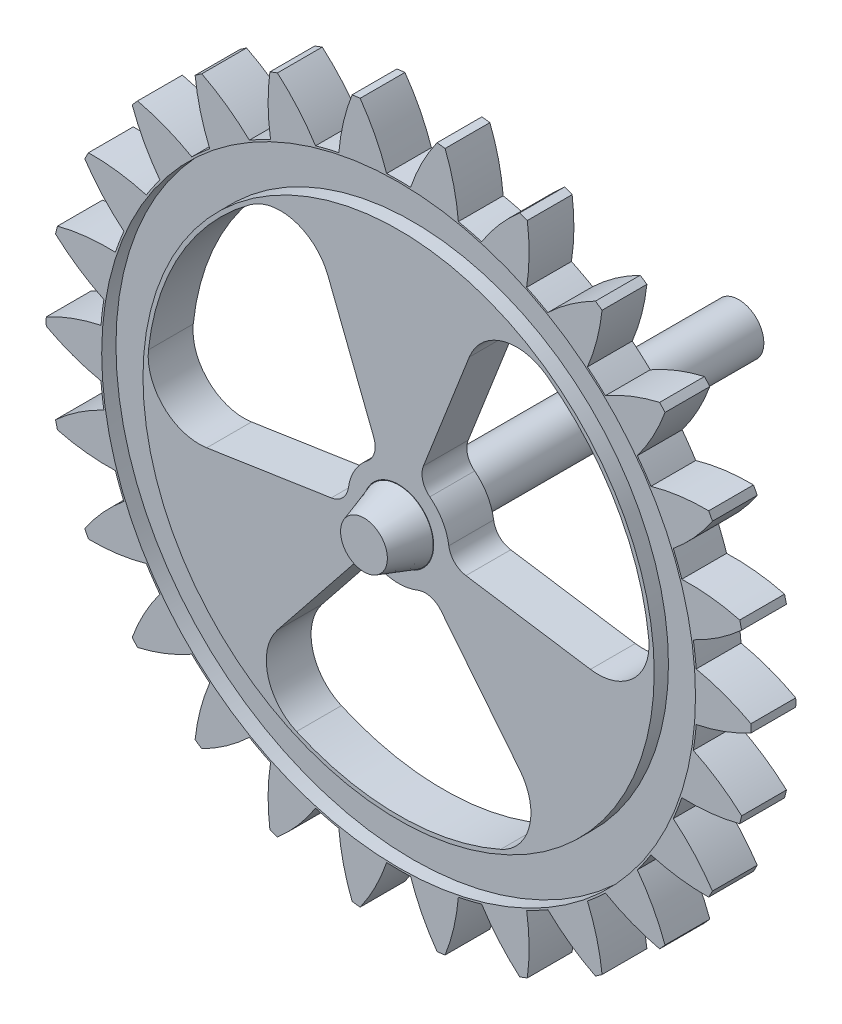
SolidWorks part; units mm, degrees
ref_plane "Plan de face" through (0, 0, 0) normal (0, 0, 1) x (1, 0, 0)
ref_plane "Plan de dessus" through (0, 0, 0) normal (0, 1, 0) x (1, 0, 0)
ref_plane "Plan de droite" through (0, 0, 0) normal (1, 0, 0) x (0, 0, -1)
sketch "Esquisse1" plane through (0, 0, 0) normal (0, 0, 1) x (1, 0, 0)
  circle A0 centre (0, 0) radius 3.4597
  circle A1 centre (0, 0) radius 0.3447
extrude "Boss.-Extru.1" add sketch "Esquisse1" along normal blind 0.44
sketch "Esquisse2" plane through (0, 0, 0.44) normal (0, 0, 1) x (1, 0, 0)
  line L0 (0, 0) -> (0, 4.2515) construction
  arc A0 (0.4748, 3.565) -> (-0.4748, 3.565) centre (0, 0) ccw
  arc A1 (0.1178, 2.9293) -> (-0.1178, 2.9293) centre (0, 0) ccw
  arc A2 (0.4748, 3.565) -> (0.1178, 2.9293) centre (1.9916, 2.2952) ccw
  arc A3 (-0.4748, 3.565) -> (-0.1178, 2.9293) centre (-1.9916, 2.2952) cw
extrude "Enlèv. mat.-Extru.1" cut sketch "Esquisse2" against normal blind 0.44
pattern_circular "Répétition circulaire1" count 26 over 360 about axis through (0, 0, 0) along (0, 0, 1) of "Enlèv. mat.-Extru.1"
sketch "Esquisse3" plane through (0, 0, 0.44) normal (0, 0, 1) x (1, 0, 0)
  line L0 (0, 0) -> (0, 2.47) construction
  line L1 (0.6941, 1.7745) -> (0.2436, 0.6227)
  line L2 (-0.6941, 1.7745) -> (-0.2436, 0.6227)
  line L3 (1.8838, -0.2862) -> (0.661, -0.1004)
  line L4 (1.1897, -1.4884) -> (0.4175, -0.5223)
  line L5 (-1.1897, -1.4884) -> (-0.4175, -0.5223)
  line L6 (-1.8838, -0.2862) -> (-0.661, -0.1004)
  arc A0 (-0.3066, 0.3923) -> (-0.493, 0.0694) centre (0, 0) ccw
  arc A1 (-1.4541, 1.9966) -> (-2.4561, 0.261) centre (0, 0) ccw
  arc A2 (-1.4541, 1.9966) -> (-0.6941, 1.7745) centre (-1.1598, 1.5924) cw
  arc A3 (0.6941, 1.7745) -> (1.4541, 1.9966) centre (1.1598, 1.5924) cw
  arc A4 (0.3066, 0.3923) -> (0.2436, 0.6227) centre (0.4298, 0.5498) cw
  arc A5 (-0.3066, 0.3923) -> (-0.2436, 0.6227) centre (-0.4298, 0.5498) ccw
  arc A6 (0.493, 0.0694) -> (0.661, -0.1004) centre (0.6911, 0.0973) ccw
  arc A7 (0.1864, -0.4617) -> (0.4175, -0.5223) centre (0.2613, -0.6471) cw
  arc A8 (1.1897, -1.4884) -> (1.002, -2.2576) centre (0.7992, -1.8006) cw
  arc A9 (2.4561, 0.261) -> (1.8838, -0.2862) centre (1.9589, 0.2082) cw
  arc A10 (-0.1864, -0.4617) -> (-0.4175, -0.5223) centre (-0.2613, -0.6471) ccw
  arc A11 (-0.493, 0.0694) -> (-0.661, -0.1004) centre (-0.6911, 0.0973) cw
  arc A12 (-1.8838, -0.2862) -> (-2.4561, 0.261) centre (-1.9589, 0.2082) cw
  arc A13 (-1.002, -2.2576) -> (-1.1897, -1.4884) centre (-0.7992, -1.8006) cw
  arc A14 (-1.002, -2.2576) -> (1.002, -2.2576) centre (0, 0) ccw
  arc A15 (2.4561, 0.261) -> (1.4541, 1.9966) centre (0, 0) ccw
  arc A16 (0.493, 0.0694) -> (0.3066, 0.3923) centre (0, 0) ccw
  arc A17 (-0.1864, -0.4617) -> (0.1864, -0.4617) centre (0, 0) ccw
  point P13 (0.1814, 0.4637)
  point P16 (-0.1814, 0.4637)
  dimension "D1" = 0.5
  dimension "D2" = 0.2
extrude "Enlèv. mat.-Extru.2" cut sketch "Esquisse3" against normal blind 0.44
sketch "Esquisse4" plane through (0, 0, 0.44) normal (0, 0, 1) x (1, 0, 0)
  circle A0 centre (0, 0) radius 2.5098
  circle A1 centre (0, 0) radius 2.9152
extrude "Enlèv. mat.-Extru.3" cut sketch "Esquisse4" against normal blind 0.14
sketch "Esquisse5" plane through (0, 0, 0) normal (0, 0, -1) x (-1, 0, 0)
  circle A0 centre (0, 0) radius 2.8343
  circle A1 centre (0, 0) radius 2.5486
extrude "Enlèv. mat.-Extru.4" cut sketch "Esquisse5" against normal blind 0.14
sketch "Esquisse6" plane through (0, 0, 0.44) normal (0, 0, 1) x (1, 0, 0)
  circle A0 centre (0, 0) radius 0.3402
extrude "Boss.-Extru.2" add sketch "Esquisse6" along normal blind 0.34 draft 18 separate body
sketch "Esquisse7" plane through (0, 0, 0.44) normal (0, 0, -1) x (-1, 0, 0)
  circle A0 centre (0, 0) radius 0.2464
extrude "Boss.-Extru.3" add sketch "Esquisse7" along normal blind 3.34
